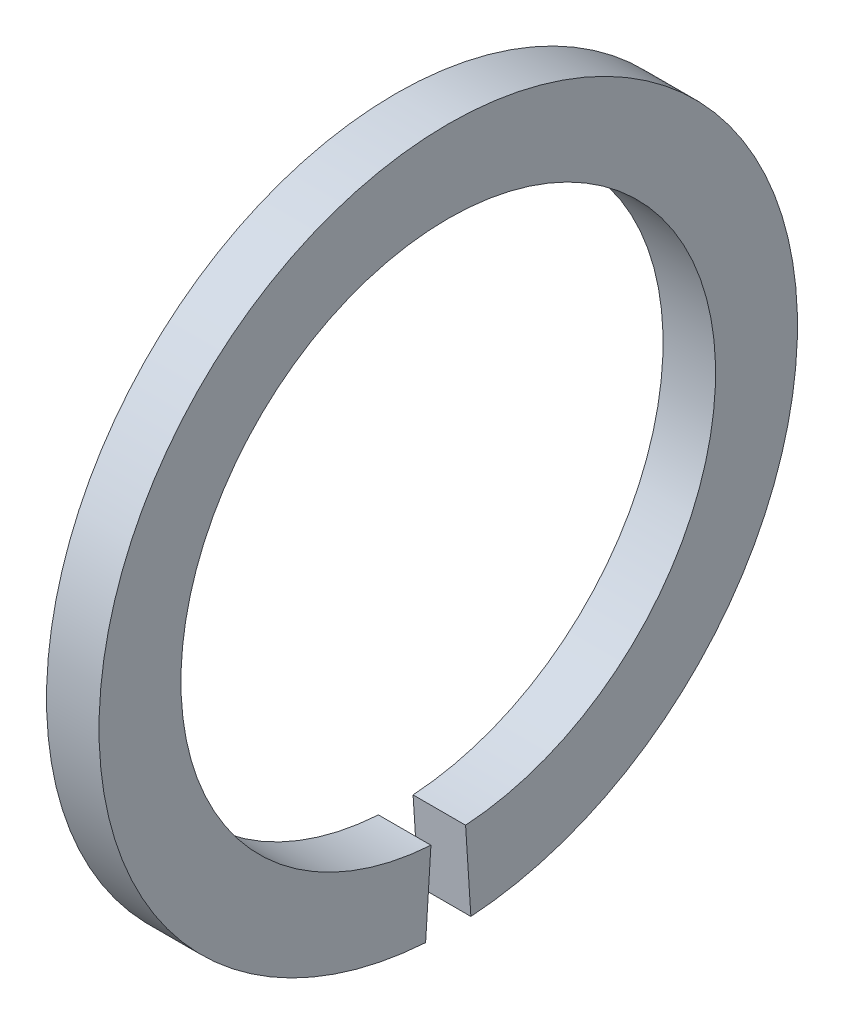
SolidWorks part; units mm, degrees
ref_plane "Front Plane" through (0, 0, 0) normal (0, 0, 1) x (1, 0, 0)
ref_plane "Top Plane" through (0, 0, 0) normal (0, 1, 0) x (1, 0, 0)
ref_plane "Right Plane" through (0, 0, 0) normal (1, 0, 0) x (0, 0, -1)
sketch "Sketch1" plane through (0, 0, 0) normal (1, 0, 0) x (0, 0, -1)
  line L0 (-0.3597, -5.5383) -> (-0.4699, -7.2348)
  line L2 (0.3597, -5.5383) -> (0.4699, -7.2348)
  arc A0 (0.3597, -5.5383) -> (-0.3597, -5.5383) centre (0, 0) ccw
  arc A1 (0.4699, -7.2348) -> (-0.4699, -7.2348) centre (0, 0) ccw
  dimension "D1" = 11.1
  dimension "D2" = 14.5
  dimension "D3" = 0.9398
  dimension "D4" = 0.7195
extrude "Boss-Extrude1" add sketch "Sketch1" along normal blind 1.09
